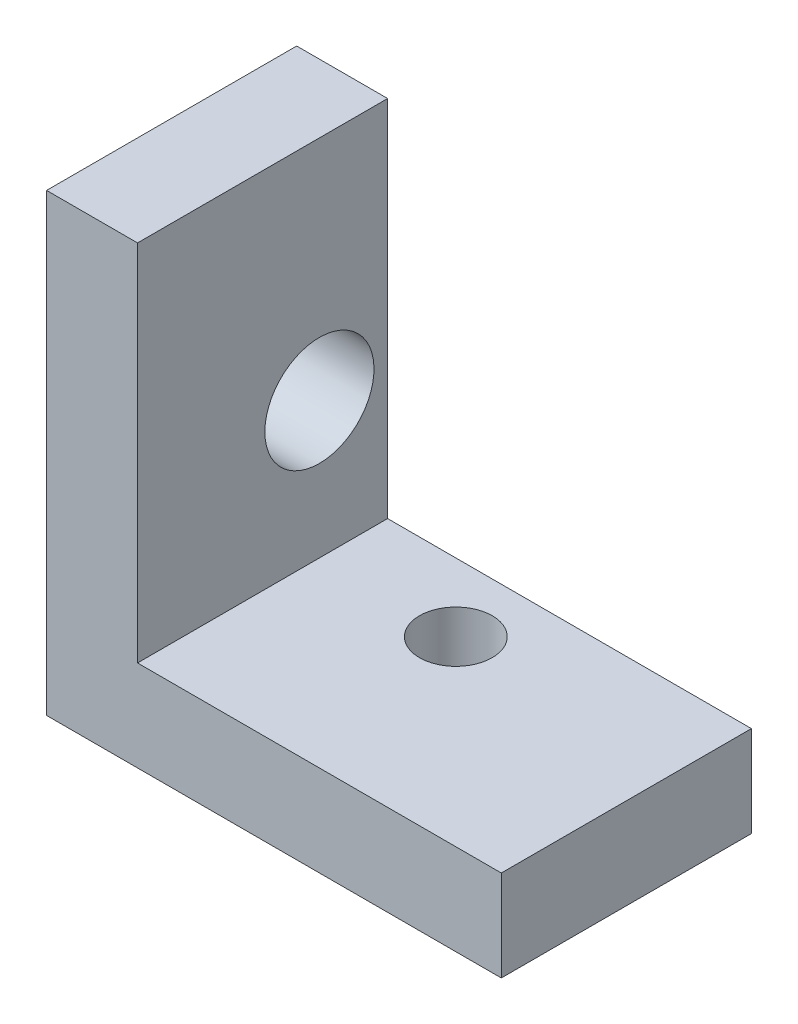
SolidWorks part; units mm, degrees
material "6061-T6 (SS)"
ref_plane "Front Plane" through (0, 0, 0) normal (0, 0, 1) x (1, 0, 0)
ref_plane "Top Plane" through (0, 0, 0) normal (0, 1, 0) x (1, 0, 0)
ref_plane "Right Plane" through (0, 0, 0) normal (1, 0, 0) x (0, 0, -1)
sketch "Sketch1" plane through (0, 0, 0) normal (0, 0, 1) x (1, 0, 0)
  line L0 (0, 0) -> (0, 10)
  line L1 (0, 10) -> (2, 10)
  line L2 (2, 10) -> (2, 2)
  line L3 (2, 2) -> (10, 2)
  line L4 (10, 2) -> (10, 0)
  line L5 (10, 0) -> (0, 0)
  dimension "D1" = 10
  dimension "D2" = 2
  dimension "D3" = 2
extrude "Boss-Extrude1" add sketch "Sketch1" along normal blind 5.5
hole_wizard "M2x0.4 Tapped Hole1" positions "Sketch2" profile "Sketch3" tap size "M2x0.4" standard "ANSI Metric" end condition up to next
sketch "Sketch2" plane through (0, 0, 0) normal (0, -1, 0) x (-1, 0, 0)
  line L0 (0, -5.5) -> (-10, -5.5) construction
  line L1 (-10, -5.5) -> (-10, 0) construction
  point P0 (-5, -1.5)
  dimension "D1" = 4
  dimension "D2" = 5
sketch "Sketch3" plane through (5, 0, 1.5) normal (1, 0, 0) x (0, 0, -1)
  line L0 (0, 0) -> (0, 2)
  line L1 (0, 2) -> (0.8, 2)
  line L2 (0.8, 2) -> (0.8, 0.425)
  line L3 (0.8, 0.425) -> (1.225, 0)
  line L5 (1.225, 0) -> (0, 0)
  line L6 (-0.8, 0.425) -> (-1.225, 0) construction
  line L11 (0, -6.35) -> (0, 107.95) construction
  dimension "Thru Tap Drill Dia." = 1.6
  dimension "Thru Tap Drill Depth" = 2
  dimension "Near C'Sink Dia." = 2.45
  dimension "Near C'Sink Angle" = 90
cosmetic thread "Hole Thread1" parameters "D2"=2
hole_wizard "M2 Clearance Hole1" positions "Sketch4" profile "Sketch5" hole size "M2" standard "ANSI Metric" end condition up to next
sketch "Sketch4" plane through (0, 0, 0) normal (-1, 0, 0) x (0, 0, 1)
  line L0 (5.5, 10) -> (5.5, 0) construction
  line L1 (5.5, 10) -> (0, 10) construction
  point P0 (1.5, 5)
  dimension "D1" = 4
  dimension "D2" = 5
sketch "Sketch5" plane through (0, 5, 1.5) normal (0, 1, 0) x (0, 0, 1)
  line L0 (0, 0) -> (0, 2)
  line L1 (0, 2) -> (1.2, 2)
  line L2 (1.2, 2) -> (1.2, 0.025)
  line L3 (1.2, 0.025) -> (1.225, 0)
  line L5 (1.225, 0) -> (0, 0)
  line L6 (-1.2, 0.025) -> (-1.225, 0) construction
  line L11 (0, -6.35) -> (0, 107.95) construction
  dimension "Thru Hole Dia." = 2.4
  dimension "Thru Hole Depth" = 2
  dimension "Near C'Sink Dia." = 2.45
  dimension "Near C'Sink Angle" = 90
